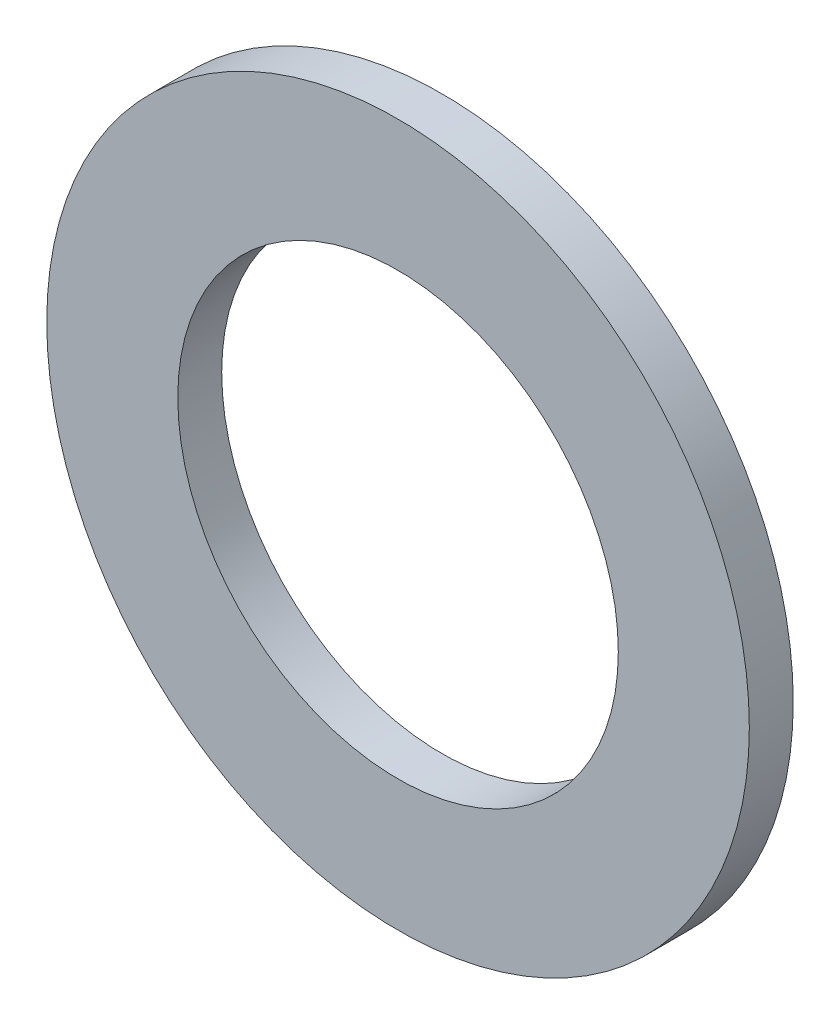
SolidWorks part; units mm, degrees
ref_plane "Front Plane" through (0, 0, 0) normal (0, 0, 1) x (1, 0, 0)
ref_plane "Top Plane" through (0, 0, 0) normal (0, 1, 0) x (1, 0, 0)
ref_plane "Right Plane" through (0, 0, 0) normal (1, 0, 0) x (0, 0, -1)
sketch "Sketch1" plane through (0, 0, 0) normal (0, 0, 1) x (1, 0, 0)
  circle A0 centre (0, 0) radius 12.7
  circle A1 centre (0, 0) radius 7.9629
  dimension "D1" = 25.4
  dimension "ID" = 15.9258
extrude "Extrude1" add sketch "Sketch1" along normal mid plane 1.5875
sketch "Sketch2" plane through (0, 0, 0) normal (1, 0, 0) x (0, 0, -1)
  line L0 (-0.7937, -7.9629) -> (0.7937, -7.9629) construction
  line L3 (0.7937, 7.9629) -> (-0.7937, 7.9629) construction
  line L5 (-0.7937, -7.9629) -> (0.7937, -7.9629)
  line L6 (0.7937, 7.9629) -> (-0.7937, 7.9629)
sketch "Sketch4" plane through (0, 0, 0.7937) normal (0, 0, 1) x (1, 0, 0)
  line L0 (0, 0) -> (-5.6306, 5.6306)
  line L1 (0, -1.7463) -> (0, 1.7463) construction
  circle A0 centre (0, 0) radius 7.9629 construction
  dimension "D1" = 45
